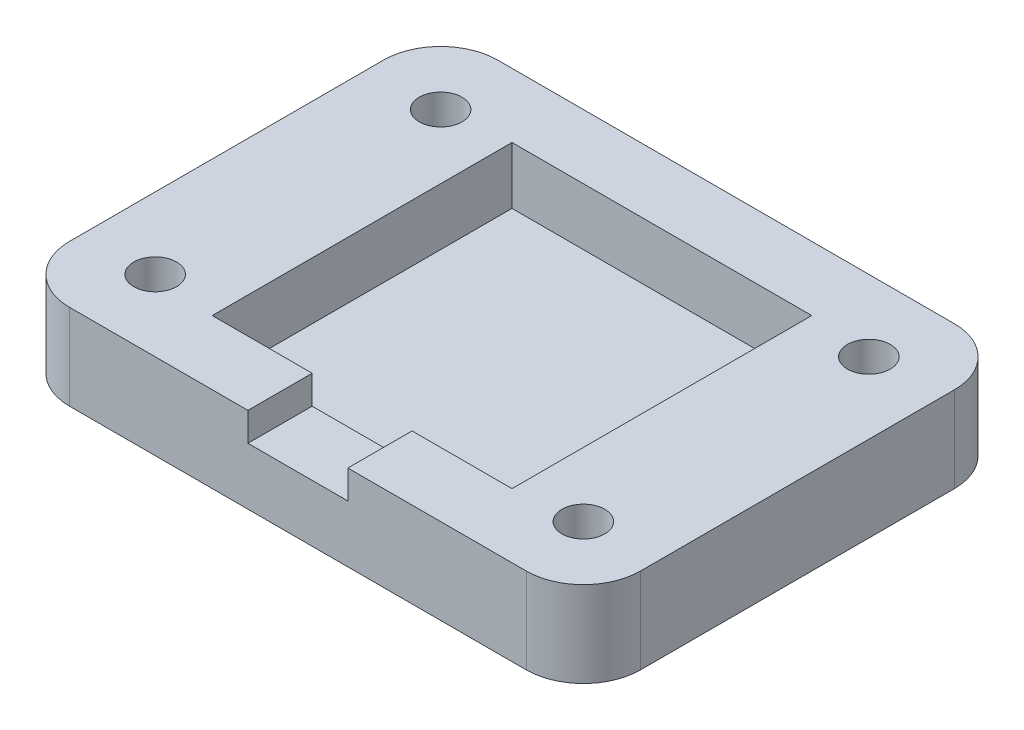
SolidWorks part; units mm, degrees
ref_plane "Front" through (0, 0, 0) normal (0, 0, 1) x (1, 0, 0)
ref_plane "Top" through (0, 0, 0) normal (0, 1, 0) x (1, 0, 0)
ref_plane "Right" through (0, 0, 0) normal (1, 0, 0) x (0, 0, -1)
sketch "Sketch1" plane through (0, 0, 0) normal (0, 1, 0) x (1, 0, 0)
  line L1 (0, 0) -> (40, 0)
  line L2 (0, 0) -> (0, 30)
  line L3 (0, 30) -> (40, 30)
  line L4 (40, 0) -> (40, 30)
  dimension "D1" = 40
  dimension "D2" = 30
extrude "Boss-Extrude1" add sketch "Sketch1" along normal blind 6
sketch "Sketch2" plane through (0, 6, 0) normal (0, 1, 0) x (1, 0, 0)
  line L0 (20, 30) -> (20, 0) construction
  line L1 (40, 30) -> (0, 30) construction
  line L2 (0, 0) -> (40, 0) construction
  line L3 (0, 15) -> (40, 15) construction
  line L4 (0, 30) -> (0, 0) construction
  line L5 (40, 0) -> (40, 30) construction
  circle A0 centre (5, 5) radius 1.5
  circle A1 centre (5, 25) radius 1.5
  circle A2 centre (35, 5) radius 1.5
  circle A3 centre (35, 25) radius 1.5
  dimension "D1" = 3
  dimension "D2" = 5
  dimension "D3" = 5
extrude "Cut-Extrude1" cut sketch "Sketch2" against normal up to surface (6 mm away) up to face at (20, 0, -15)
fillet "Fillet1" radius 4 4 edges at (0, 3, -30) (40, 3, -30) (40, 3, 0) (0, 3, 0)
sketch "Sketch3" plane through (0, 6, 0) normal (0, 1, 0) x (1, 0, 0)
  line L0 (4, 0) -> (36, 0) construction
  line L1 (9.5, 4.5) -> (30.5, 4.5)
  line L2 (9.5, 4.5) -> (9.5, 25.5)
  line L3 (9.5, 25.5) -> (30.5, 25.5)
  line L4 (30.5, 4.5) -> (30.5, 25.5)
  line L5 (0, 26) -> (0, 4) construction
  point P4 (20, 4.5)
  point P7 (20, 0)
  point P8 (9.5, 15)
  point P11 (0, 15)
  dimension "D1" = 21
  dimension "D2" = 21
extrude "Cut-Extrude2" cut sketch "Sketch3" against normal blind 4
sketch "Sketch4" plane through (0, 6, 0) normal (0, 1, 0) x (1, 0, 0)
  line L0 (9.5, 4.5) -> (30.5, 4.5) construction
  line L1 (16.5, 4.5) -> (23.5, 4.5)
  line L2 (16.5, 4.5) -> (16.5, 0)
  line L3 (16.5, 0) -> (23.5, 0)
  line L4 (23.5, 4.5) -> (23.5, 0)
  line L5 (4, 0) -> (36, 0) construction
  dimension "D1" = 7
  dimension "D2" = 7
extrude "Cut-Extrude3" cut sketch "Sketch4" against normal blind 2
